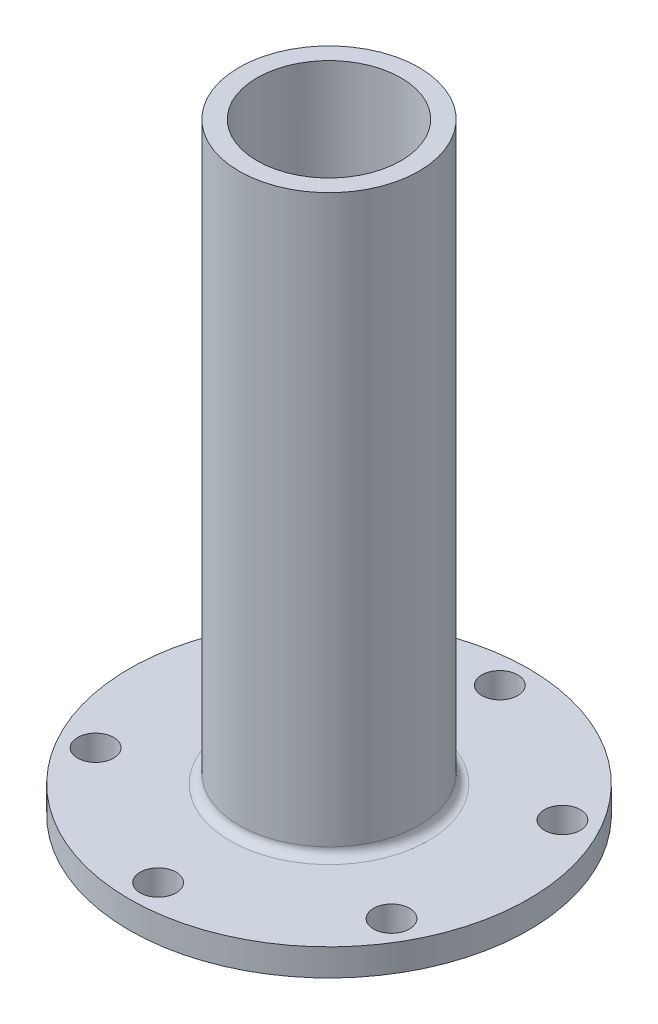
SolidWorks part; units mm, degrees
material "6061-O (SS)"
ref_plane "Front Plane" through (0, 0, 0) normal (0, 0, 1) x (1, 0, 0)
ref_plane "Top Plane" through (0, 0, 0) normal (0, 1, 0) x (1, 0, 0)
ref_plane "Right Plane" through (0, 0, 0) normal (1, 0, 0) x (0, 0, -1)
sketch "Sketch1" plane through (0, 0, 0) normal (0, 1, 0) x (1, 0, 0)
  circle A0 centre (0, 0) radius 15.875
  circle A1 centre (0, 0) radius 12.7
extrude "Boss-Extrude1" add sketch "Sketch1" along normal blind 101.6
sketch "Sketch2" plane through (0, 0, 0) normal (0, -1, 0) x (-1, 0, 0)
  circle A0 centre (0, 0) radius 12.7
  circle A1 centre (0, 0) radius 35.2425
extrude "Boss-Extrude2" add sketch "Sketch2" along normal blind 4.7625
fillet "Fillet1" radius 1.5875 1 edges at (0, 0, 15.875)
sketch "Sketch3" plane through (0, -4.7625, 0) normal (0, -1, 0) x (-1, 0, 0)
  circle A1 centre (0, -30.1625) radius 3.175
  circle A2 centre (-26.1215, -15.0812) radius 3.175
  circle A3 centre (-26.1215, 15.0813) radius 3.175
  circle A4 centre (0, 30.1625) radius 3.175
  circle A5 centre (26.1215, 15.0812) radius 3.175
  circle A6 centre (26.1215, -15.0813) radius 3.175
  point P17 (0, 0)
  dimension "D1" = 6
extrude "Cut-Extrude1" cut sketch "Sketch3" against normal blind 4.7625
